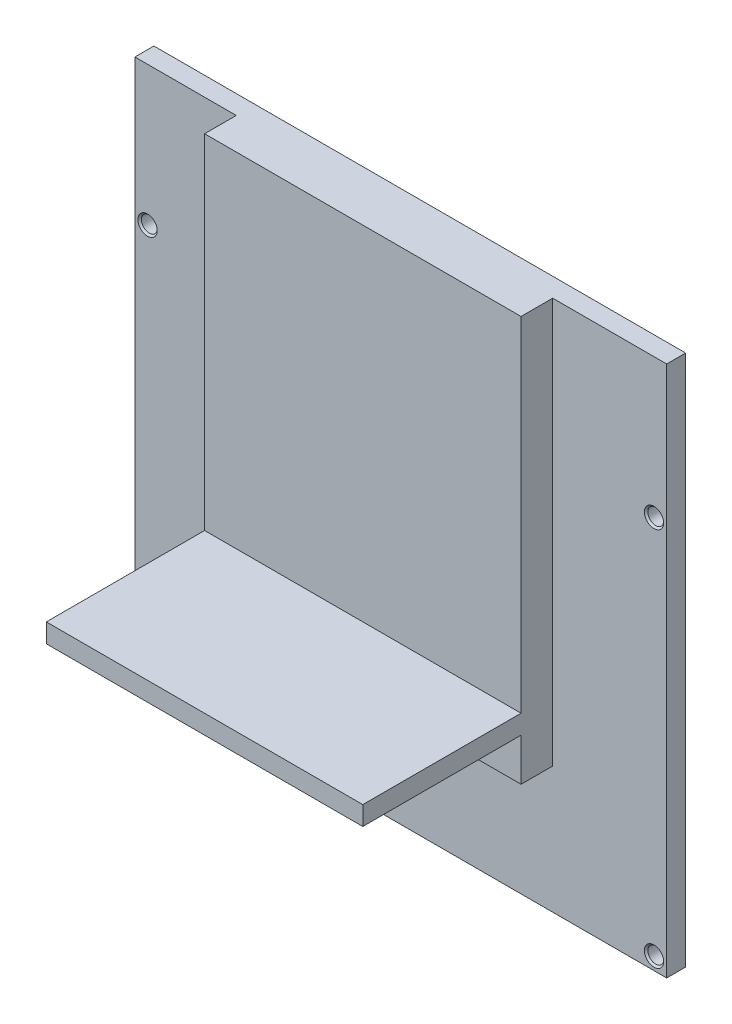
SolidWorks part; units mm, degrees
ref_plane "前视基准面" through (0, 0, 0) normal (0, 0, 1) x (1, 0, 0)
ref_plane "上视基准面" through (0, 0, 0) normal (0, 1, 0) x (1, 0, 0)
ref_plane "右视基准面" through (0, 0, 0) normal (1, 0, 0) x (0, 0, -1)
sketch "草图1" plane through (0, 0, 0) normal (0, 0, 1) x (1, 0, 0)
  line L0 (-29.1326, -10.4353) -> (20.8674, -10.4353)
  line L1 (-29.1326, 15.5647) -> (20.8674, 15.5647)
  line L2 (-29.1326, 15.5647) -> (-29.1326, -20.4353)
  line L3 (-29.1326, -20.4353) -> (20.8674, -20.4353)
  line L4 (20.8674, 15.5647) -> (20.8674, -20.4353)
  line L5 (-29.1326, -7.4353) -> (20.8674, -7.4353)
  line L6 (-29.1326, 2.5647) -> (20.8674, 2.5647)
  line L7 (-29.1326, 5.5647) -> (20.8674, 5.5647)
  dimension "D1" = 50
  dimension "D2" = 36
  dimension "D3" = 10
  dimension "D4" = 10
  dimension "D5" = 3
  dimension "D6" = 3
sketch "草图2" plane through (0, 0, 0) normal (0, 0, 1) x (1, 0, 0)
  line L0 (-35.1326, 18.5647) -> (26.8674, 18.5647)
  line L1 (26.8674, 18.5647) -> (26.8674, -26.4353)
  line L2 (26.8674, -26.4353) -> (-35.1326, -26.4353)
  line L3 (-35.1326, -26.4353) -> (-35.1326, 18.5647)
  line L4 (-29.1326, 15.5647) -> (20.8674, 15.5647) construction
  line L5 (-29.1326, -20.4353) -> (20.8674, -20.4353) construction
  line L6 (20.8674, 15.5647) -> (20.8674, -20.4353) construction
  line L7 (-29.1326, 15.5647) -> (-29.1326, -20.4353) construction
  dimension "D1" = 3
  dimension "D2" = 6
  dimension "D3" = 6
  dimension "D4" = 6
extrude "凸台-拉伸3" add sketch "草图2" along normal blind 8
sketch "草图3" plane through (0, -26.4353, 0) normal (0, -1, 0) x (1, 0, 0)
  line L1 (-32.1326, 8) -> (-29.1276, 8)
  line L2 (-32.1326, 8) -> (-32.1326, 3)
  line L3 (-32.1326, 3) -> (-29.1276, 3)
  line L4 (-29.1276, 8) -> (-29.1276, 3)
  line L6 (-35.1326, 8) -> (26.8674, 8) construction
  line L7 (-35.1326, 8) -> (-35.1326, 0) construction
  line L8 (20.8625, 8) -> (23.8674, 8)
  line L9 (20.8625, 8) -> (20.8625, 3)
  line L10 (20.8625, 3) -> (23.8674, 3)
  line L11 (23.8674, 8) -> (23.8674, 3)
  line L12 (26.8674, 8) -> (26.8674, 0) construction
  dimension "D1" = 5
  dimension "D2" = 3.005
  dimension "D3" = 3
  dimension "D4" = 3.005
  dimension "D5" = 5
  dimension "D6" = 3
extrude "切除-拉伸1" cut sketch "草图3" against normal through all
sketch "草图5" plane through (0, 0, 0) normal (0, 0, -1) x (-1, 0, 0)
  line L0 (3.1326, 18.5647) -> (3.1326, -26.4353) construction
  line L1 (-26.8674, -3.9353) -> (35.1326, -3.9353) construction
  line L3 (-38.8674, -45.4353) -> (-38.8674, 18.5647)
  line L4 (-38.8674, 18.5647) -> (45.1326, 18.5647)
  line L5 (45.1326, 18.5647) -> (45.1326, -45.4353)
  line L6 (3.1326, -45.4353) -> (-38.8674, -45.4353)
  line L7 (3.1326, -45.4353) -> (45.1326, -45.4353)
  line L8 (-26.8674, -26.4353) -> (-26.8674, 18.5647) construction
  line L9 (-26.8674, 18.5647) -> (35.1326, 18.5647) construction
  dimension "D1" = 42
  dimension "D2" = 30
  dimension "D3" = 64
extrude "凸台-拉伸4" add sketch "草图5" against normal blind 3 contours L5 L7 L6 L3 L4
sketch "草图6" plane through (0, -26.4353, 0) normal (0, -1, 0) x (1, 0, 0)
  line L4 (-35.1326, 8) -> (-35.1326, 3)
  line L5 (-35.1326, 3) -> (-32.1326, 3)
  line L6 (-32.1326, 3) -> (-32.1326, 8)
  line L7 (-32.1326, 8) -> (-35.1326, 8)
  line L8 (-35.1326, 8) -> (-35.1326, 3)
  line L9 (-35.1326, 3) -> (-32.1326, 3)
  line L10 (-32.1326, 3) -> (-32.1326, 8)
  line L11 (-32.1326, 8) -> (-35.1326, 8)
  dimension "D1" = 0
extrude "凸台-拉伸5" add sketch "草图6" along normal blind 2
sketch "草图7" plane through (0, -26.4353, 0) normal (0, -1, 0) x (1, 0, 0)
  line L4 (23.8674, 8) -> (23.8674, 3)
  line L5 (23.8674, 3) -> (26.8674, 3)
  line L6 (26.8674, 3) -> (26.8674, 8)
  line L7 (26.8674, 8) -> (23.8674, 8)
  line L8 (23.8674, 8) -> (23.8674, 3)
  line L9 (23.8674, 3) -> (26.8674, 3)
  line L10 (26.8674, 3) -> (26.8674, 8)
  line L11 (26.8674, 8) -> (23.8674, 8)
  dimension "D1" = 0
extrude "凸台-拉伸6" add sketch "草图7" along normal blind 2
sketch "草图8" plane through (0, -26.4353, 0) normal (0, -1, 0) x (1, 0, 0)
  line L4 (-29.1276, 8) -> (-29.1276, 3)
  line L5 (-29.1276, 3) -> (20.8625, 3)
  line L6 (20.8625, 3) -> (20.8625, 8)
  line L7 (20.8625, 8) -> (-29.1276, 8)
  line L8 (-29.1276, 8) -> (-29.1276, 3)
  line L9 (-29.1276, 3) -> (20.8625, 3)
  line L10 (20.8625, 3) -> (20.8625, 8)
  line L11 (20.8625, 8) -> (-29.1276, 8)
  dimension "D1" = 0
extrude "凸台-拉伸7" add sketch "草图8" along normal blind 2
sketch "草图9" plane through (0, -28.4353, 0) normal (0, -1, 0) x (1, 0, 0)
  line L4 (-32.1326, 8) -> (-35.1326, 8)
  line L5 (-35.1326, 8) -> (-35.1326, 3)
  line L6 (-35.1326, 3) -> (-32.1326, 3)
  line L7 (-32.1326, 3) -> (-32.1326, 8)
  line L8 (-32.1326, 8) -> (-35.1326, 8)
  line L9 (-35.1326, 8) -> (-35.1326, 3)
  line L10 (-35.1326, 3) -> (-32.1326, 3)
  line L11 (-32.1326, 3) -> (-32.1326, 8)
  dimension "D1" = 0
extrude "切除-拉伸2" cut sketch "草图9" against normal through all
sketch "草图10" plane through (0, -28.4353, 0) normal (0, -1, 0) x (1, 0, 0)
  line L4 (26.8674, 8) -> (23.8674, 8)
  line L5 (23.8674, 8) -> (23.8674, 3)
  line L6 (23.8674, 3) -> (26.8674, 3)
  line L7 (26.8674, 3) -> (26.8674, 8)
  line L8 (26.8674, 8) -> (23.8674, 8)
  line L9 (23.8674, 8) -> (23.8674, 3)
  line L10 (23.8674, 3) -> (26.8674, 3)
  line L11 (26.8674, 3) -> (26.8674, 8)
  dimension "D1" = 0
extrude "切除-拉伸4" cut sketch "草图10" against normal through all
sketch "草图11" plane through (0, -28.4353, 0) normal (0, -1, 0) x (1, 0, 0)
  line L4 (20.8625, 8) -> (-29.1276, 8)
  line L5 (-29.1276, 8) -> (-29.1276, 3)
  line L6 (-29.1276, 3) -> (20.8625, 3)
  line L7 (20.8625, 3) -> (20.8625, 8)
  line L8 (20.8625, 8) -> (-29.1276, 8)
  line L9 (-29.1276, 8) -> (-29.1276, 3)
  line L10 (-29.1276, 3) -> (20.8625, 3)
  line L11 (20.8625, 3) -> (20.8625, 8)
  dimension "D1" = 0
extrude "凸台-拉伸8" add sketch "草图11" along normal blind 17
sketch "草图12" plane through (0, 0, 8) normal (0, 0, 1) x (1, 0, 0)
  line L0 (-29.1276, -45.4353) -> (20.8625, -45.4353)
  line L1 (20.8625, -45.4353) -> (20.8625, -42.4353)
  line L2 (20.8625, 18.5647) -> (20.8625, -45.4353) construction
  line L3 (20.8625, -42.4353) -> (-29.1276, -42.4353)
  line L4 (-29.1276, 18.5647) -> (-29.1276, -45.4353) construction
  line L5 (-29.1276, -42.4353) -> (-29.1276, -45.4353)
  dimension "D1" = 3
extrude "凸台-拉伸9" add sketch "草图12" along normal blind 25
sketch "草图16" plane through (0, -42.4353, 0) normal (0, 1, 0) x (1, 0, 0)
  line L4 (20.8625, -8) -> (-29.1276, -8)
  line L5 (-29.1276, -8) -> (-29.1276, -33)
  line L6 (-29.1276, -33) -> (20.8625, -33)
  line L7 (20.8625, -33) -> (20.8625, -8)
  line L8 (20.8625, -8) -> (-29.1276, -8)
  line L9 (-29.1276, -8) -> (-29.1276, -33)
  line L10 (-29.1276, -33) -> (20.8625, -33)
  line L11 (20.8625, -33) -> (20.8625, -8)
  dimension "D1" = 0
extrude "凸台-拉伸10" add sketch "草图16" along normal blind 3 from offset 3.72
sketch "草图17" plane through (0, -38.7153, 0) normal (0, -1, 0) x (1, 0, 0)
  line L4 (20.8625, 8) -> (20.8625, 33)
  line L5 (20.8625, 33) -> (-29.1276, 33)
  line L6 (-29.1276, 33) -> (-29.1276, 8)
  line L7 (-29.1276, 8) -> (20.8625, 8)
  line L8 (20.8625, 8) -> (20.8625, 33)
  line L9 (20.8625, 33) -> (-29.1276, 33)
  line L10 (-29.1276, 33) -> (-29.1276, 8)
  line L11 (-29.1276, 8) -> (20.8625, 8)
  dimension "D1" = 0
extrude "切除-拉伸5" cut sketch "草图17" along normal through all
sketch "草图18" plane through (0, -45.4353, 0) normal (0, -1, 0) x (1, 0, 0)
  line L1 (-45.1326, 3) -> (38.8674, 3)
  line L2 (-45.1326, 3) -> (-45.1326, 0)
  line L3 (-45.1326, 0) -> (38.8674, 0)
  line L4 (38.8674, 3) -> (38.8674, 0)
extrude "凸台-拉伸11" add sketch "草图18" along normal blind 20
sketch "草图19" plane through (0, 0, 3) normal (0, 0, 1) x (1, 0, 0)
  line L0 (-45.1326, 18.5647) -> (-45.1326, -65.4353) construction
  line L2 (38.8674, -65.4353) -> (-45.1326, -65.4353) construction
  line L3 (38.8674, -65.4353) -> (38.8674, 18.5647) construction
  line L4 (38.8674, -65.4353) -> (38.8674, 18.5647) construction
  point P0 (-43.1326, -63.4353)
  point P1 (36.8674, -63.4353)
  point P6 (36.8674, -3.4353)
  point P12 (-43.1326, -3.4353)
  dimension "D1" = 2
  dimension "D2" = 2
  dimension "D3" = 2
  dimension "D4" = 2
  dimension "D5" = 2
  dimension "D6" = 60
  dimension "D7" = 60
  dimension "D8" = 2
hole_wizard "M3 螺纹孔2" positions "草图20" profile "草图21" tap size "M3" standard "GB" end condition through all
sketch "草图20" plane through (0, 0, 3) normal (0, 0, 1) x (1, 0, 0)
  point P0 (-43.1326, -3.4353)
  point P3 (36.8674, -3.4353)
  point P6 (36.8674, -63.4353)
  point P9 (-43.1326, -63.4353)
sketch "草图21" plane through (-43.1326, -3.4353, 3) normal (1, 0, 0) x (0, -1, 0)
  line L0 (0, 0) -> (0, 3)
  line L1 (0, 3) -> (1.25, 3)
  line L2 (1.25, 3) -> (1.25, 0.275)
  line L3 (1.25, 0.275) -> (1.525, 0)
  line L5 (1.525, 0) -> (0, 0)
  line L6 (-1.25, 0.275) -> (-1.525, 0) construction
  line L11 (0, -6.35) -> (0, 107.95) construction
  dimension "通孔螺纹孔钻头直径" = 2.5
  dimension "通孔螺纹孔钻头深度" = 3
  dimension "近端锥形沉头孔直径" = 3.05
  dimension "近端锥形沉头孔角度" = 90
cosmetic thread "孔螺蚊线5" parameters "D2"=3
cosmetic thread "孔螺蚊线6" parameters "D2"=3
cosmetic thread "孔螺蚊线7" parameters "D2"=3
cosmetic thread "孔螺蚊线8" parameters "D2"=3
